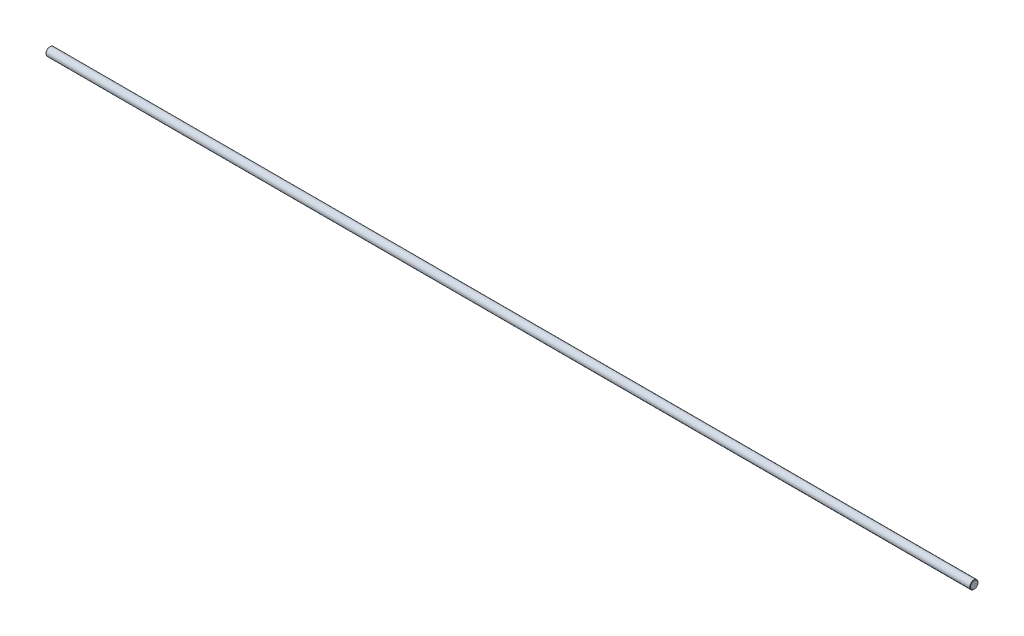
SolidWorks part; units mm, degrees
ref_plane "Front Plane" through (0, 0, 0) normal (0, 0, 1) x (1, 0, 0)
ref_plane "Top Plane" through (0, 0, 0) normal (0, 1, 0) x (1, 0, 0)
ref_plane "Right Plane" through (0, 0, 0) normal (1, 0, 0) x (0, 0, -1)
sketch "Sketch2" plane through (0, 0, 0) normal (1, 0, 0) x (0, 0, -1)
  circle A0 centre (0, 0) radius 6
  dimension "D1" = 12
extrude "Boss-Extrude1" add sketch "Sketch2" along normal blind 1340
chamfer "Chamfer1" distance 0.5 angle 45 2 edges at (0, 0, -6) (1340, 0, -6)
